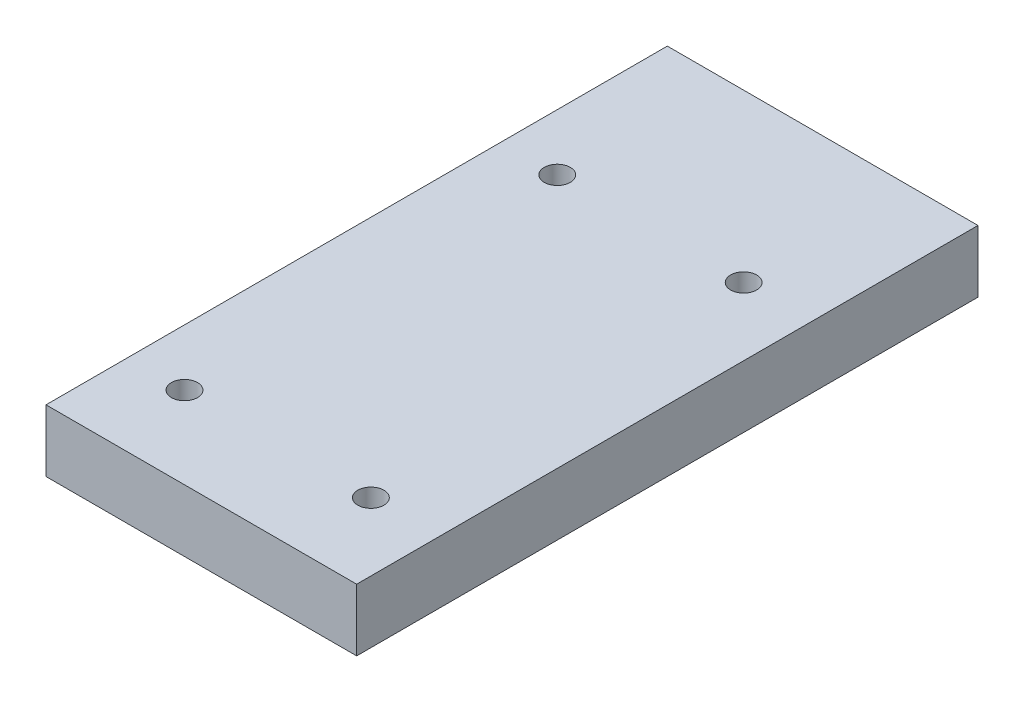
SolidWorks part; units mm, degrees
ref_plane "Front Plane" through (0, 0, 0) normal (0, 0, 1) x (1, 0, 0)
ref_plane "Top Plane" through (0, 0, 0) normal (0, 1, 0) x (1, 0, 0)
ref_plane "Right Plane" through (0, 0, 0) normal (1, 0, 0) x (0, 0, -1)
sketch "Sketch3" plane through (0, 0, 0) normal (0, 1, 0) x (1, 0, 0)
  line L1 (0, 0) -> (25, 0)
  line L2 (0, 0) -> (0, 50)
  line L3 (0, 50) -> (25, 50)
  line L4 (25, 0) -> (25, 50)
  dimension "D1" = 25
  dimension "D2" = 50
extrude "Boss-Extrude2" add sketch "Sketch3" along normal blind 5
sketch "Sketch4" plane through (0, 0, 0) normal (0, 1, 0) x (1, 0, 0)
  line L0 (4.5462, 6.5968) -> (19.5462, 6.5968) construction
  line L1 (4.5462, 36.5968) -> (19.5462, 36.5968) construction
  line L2 (12.0462, 36.5968) -> (12.0462, 6.5968) construction
  circle A0 centre (4.5462, 6.5968) radius 1.05
  circle A1 centre (4.5462, 36.5968) radius 1.05
  circle A2 centre (19.5462, 36.5968) radius 1.05
  circle A3 centre (19.5462, 6.5968) radius 1.05
  dimension "D1" = 2.1
  dimension "D2" = 30
  dimension "D3" = 15
  dimension "D4" = 15
extrude "Cut-Extrude3" cut sketch "Sketch4" against normal through all and the other way through all
